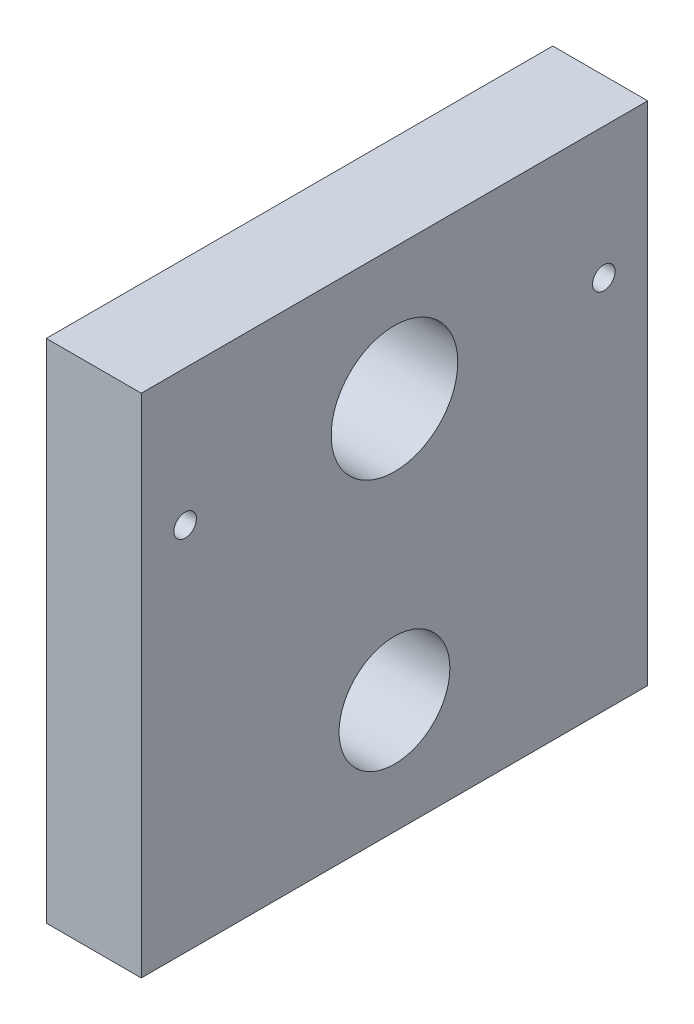
SolidWorks part; units mm, degrees
material "ABS PC"
ref_plane "Front Plane" through (0, 0, 0) normal (0, 0, 1) x (1, 0, 0)
ref_plane "Top Plane" through (0, 0, 0) normal (0, 1, 0) x (1, 0, 0)
ref_plane "Right Plane" through (0, 0, 0) normal (1, 0, 0) x (0, 0, -1)
sketch "Sketch1" plane through (0, 0, 0) normal (1, 0, 0) x (0, 0, -1)
  line L1 (-25.4, -25.4) -> (25.4, -25.4)
  line L2 (-25.4, -25.4) -> (-25.4, 25.4)
  line L3 (-25.4, 25.4) -> (25.4, 25.4)
  line L4 (25.4, -25.4) -> (25.4, 25.4)
  line L5 (-25.4, -25.4) -> (25.4, 25.4) construction
  line L6 (-25.4, 25.4) -> (25.4, -25.4) construction
  point P0 (0, 0)
  dimension "D1" = 50.8
  dimension "D2" = 50.8
extrude "Boss-Extrude1" add sketch "Sketch1" along normal blind 9.525
hole_wizard "7/16 (0.4375) Diameter Hole1" positions "Sketch9" profile "Sketch8" hole size "7/16" standard "ANSI Inch"
sketch "Sketch9" plane through (9.525, 0, 0) normal (1, 0, 0) x (0, 0, -1)
  line L0 (-25.4, -25.4) -> (25.4, -25.4) construction
  point P0 (0, -13.97)
  dimension "D1" = 11.43
sketch "Sketch8" plane through (9.525, -13.97, 0) normal (0, 1, 0) x (0, 0, -1)
  line L0 (0, 0) -> (0, 73.4425)
  line L1 (0, 73.4425) -> (5.5562, 70.104)
  line L2 (5.5562, 70.104) -> (5.5562, 0)
  line L5 (5.5562, 0) -> (0, 0)
  line L10 (0, 73.4425) -> (-5.5563, 70.104) construction
  line L11 (0, -6.35) -> (0, 107.95) construction
  dimension "Hole Dia." = 11.1125
  dimension "Hole Depth" = 70.104
  dimension "Drill Angle" = 118
hole_wizard "1/2 (0.5) Diameter Hole2" positions "Sketch3" profile "Sketch2" hole size "1/2" standard "ANSI Inch"
sketch "Sketch3" plane through (9.525, 0, 0) normal (1, 0, 0) x (0, 0, -1)
  circle A0 centre (0, -13.97) radius 5.5562 construction
  point P0 (0, 12.2301)
  dimension "D1" = 26.2001
  dimension "D2" = 0
sketch "Sketch2" plane through (9.525, 12.2301, 0) normal (0, 1, 0) x (0, 0, -1)
  line L0 (0, 0) -> (0, 73.9195)
  line L1 (0, 73.9195) -> (6.35, 70.104)
  line L2 (6.35, 70.104) -> (6.35, 0)
  line L5 (6.35, 0) -> (0, 0)
  line L10 (0, 73.9195) -> (-6.35, 70.104) construction
  line L11 (0, -6.35) -> (0, 107.95) construction
  dimension "Hole Dia." = 12.7
  dimension "Hole Depth" = 70.104
  dimension "Drill Angle" = 118
hole_wizard "#4-40 Tapped Hole1" positions "Sketch5" profile "Sketch4" tap size "#4-40" standard "ANSI Inch" end condition through all
sketch "Sketch5" plane through (9.525, 0, 0) normal (1, 0, 0) x (0, 0, -1)
  circle A0 centre (0, 12.2301) radius 6.35 construction
  point P0 (21, 12.2301)
  point P2 (-21, 11.7415)
  dimension "D1" = 0.4886
  dimension "D2" = 0
  dimension "D3" = 21
  dimension "D4" = 42
sketch "Sketch4" plane through (9.525, 12.2301, -21) normal (0, 1, 0) x (0, 0, -1)
  line L0 (0, 0) -> (0, 9.525)
  line L1 (0, 9.525) -> (1.1303, 9.525)
  line L2 (1.1303, 9.525) -> (1.1303, 0)
  line L5 (1.1303, 0) -> (0, 0)
  line L11 (0, -6.35) -> (0, 107.95) construction
  dimension "Thread Major Dia." = 2.2606
  dimension "Thru Tap Drill Depth" = 9.525
hole_wizard "#10-32 Tapped Hole1" positions "Sketch11" profile "Sketch10" tap size "#10-32" standard "ANSI Inch"
sketch "Sketch11" plane through (-0.6693, 7.9801, -25.4) normal (0, 0, -1) x (-1, 0, 0)
  line L0 (-10.1943, 17.4199) -> (-0.6693, 17.4199) construction
  line L2 (-10.1943, -33.3801) -> (-0.6693, -33.3801) construction
  line L3 (-10.1943, 17.4199) -> (-0.6693, 17.4199) construction
  point P0 (-5.4318, -27.0301)
  point P2 (-5.4318, 11.0699)
  point P6 (-5.4318, 17.4199)
  dimension "D1" = 0
  dimension "D2" = 0
  dimension "D3" = 6.35
  dimension "D4" = 6.35
sketch "Sketch10" plane through (4.7625, -19.05, -25.4) normal (1, 0, 0) x (0, 1, 0)
  line L0 (0, 0) -> (0, 13.1513)
  line L1 (0, 13.1513) -> (2.0193, 11.938)
  line L2 (2.0193, 11.938) -> (2.0193, 0)
  line L5 (2.0193, 0) -> (0, 0)
  line L10 (0, 13.1513) -> (-2.0193, 11.938) construction
  line L11 (0, -6.35) -> (0, 107.95) construction
  dimension "Tap Drill Dia." = 4.0386
  dimension "Tap Drill Depth" = 11.938
  dimension "Drill Angle" = 118
cosmetic thread "Hole Thread1" parameters "D1"=9.652, "D2"=4.826
cosmetic thread "Hole Thread2" parameters "D1"=9.652, "D2"=4.826
